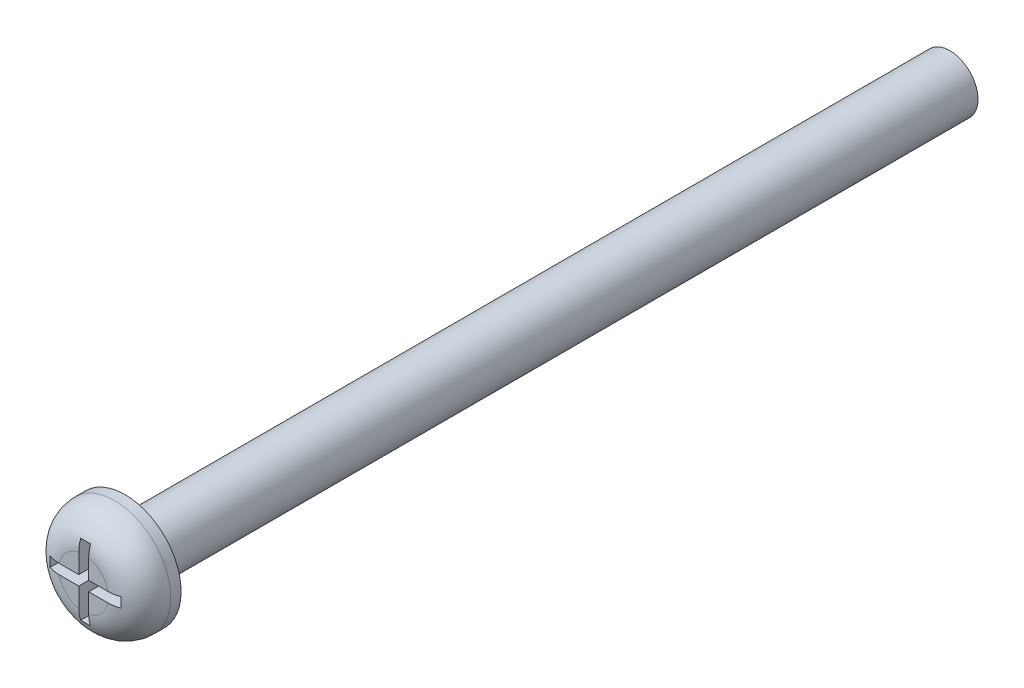
SolidWorks part; units mm, degrees
ref_plane "Front Plane" through (0, 0, 0) normal (0, 0, 1) x (1, 0, 0)
ref_plane "Top Plane" through (0, 0, 0) normal (0, 1, 0) x (1, 0, 0)
ref_plane "Right Plane" through (0, 0, 0) normal (1, 0, 0) x (0, 0, -1)
sketch "Sketch1" plane through (0, 0, 0) normal (0, 0, 1) x (1, 0, 0)
  circle A0 centre (0, 0) radius 1.7272
  dimension "D1" = 3.4544
extrude "Boss-Extrude1" add sketch "Sketch1" along normal blind 50.546
sketch "Sketch2" plane through (0, 0, 50.546) normal (0, 0, 1) x (1, 0, 0)
  circle A0 centre (0, 0) radius 3.429
  dimension "D1" = 6.858
extrude "Boss-Extrude2" add sketch "Sketch2" along normal blind 2.54
fillet "Fillet1" radius 1.905 1 edges at (3.429, 0, 53.086)
sketch "Sketch3" plane through (0, 0, 53.086) normal (0, 0, 1) x (1, 0, 0)
  line L0 (-0.3036, 0.3036) -> (-0.3036, 2.1764)
  line L1 (-2.1764, -0.3036) -> (-0.3036, -0.3036)
  line L2 (-2.1764, -0.3036) -> (-2.1764, 0.3036)
  line L3 (-2.1764, 0.3036) -> (-0.3036, 0.3036)
  line L4 (2.1764, -0.3036) -> (2.1764, 0.3036)
  line L5 (-2.1764, -0.3036) -> (2.1764, 0.3036) construction
  line L6 (-2.1764, 0.3036) -> (2.1764, -0.3036) construction
  line L7 (-0.3036, -2.1764) -> (0.3036, -2.1764)
  line L8 (-0.3036, -2.1764) -> (-0.3036, -0.3036)
  line L9 (-0.3036, 2.1764) -> (0.3036, 2.1764)
  line L10 (0.3036, -2.1764) -> (0.3036, -0.3036)
  line L11 (-0.3036, -2.1764) -> (0.3036, 2.1764) construction
  line L12 (-0.3036, 2.1764) -> (0.3036, -2.1764) construction
  line L14 (0.3036, 0.3036) -> (2.1764, 0.3036)
  line L15 (0.3036, 0.3036) -> (0.3036, 2.1764)
  line L16 (0.3036, -0.3036) -> (2.1764, -0.3036)
  point P0 (0, 0)
  point P6 (0, 0)
  dimension "D1" = 0.6071
  dimension "D2" = 4.3527
extrude "Cut-Extrude1" cut sketch "Sketch3" against normal blind 1.905
